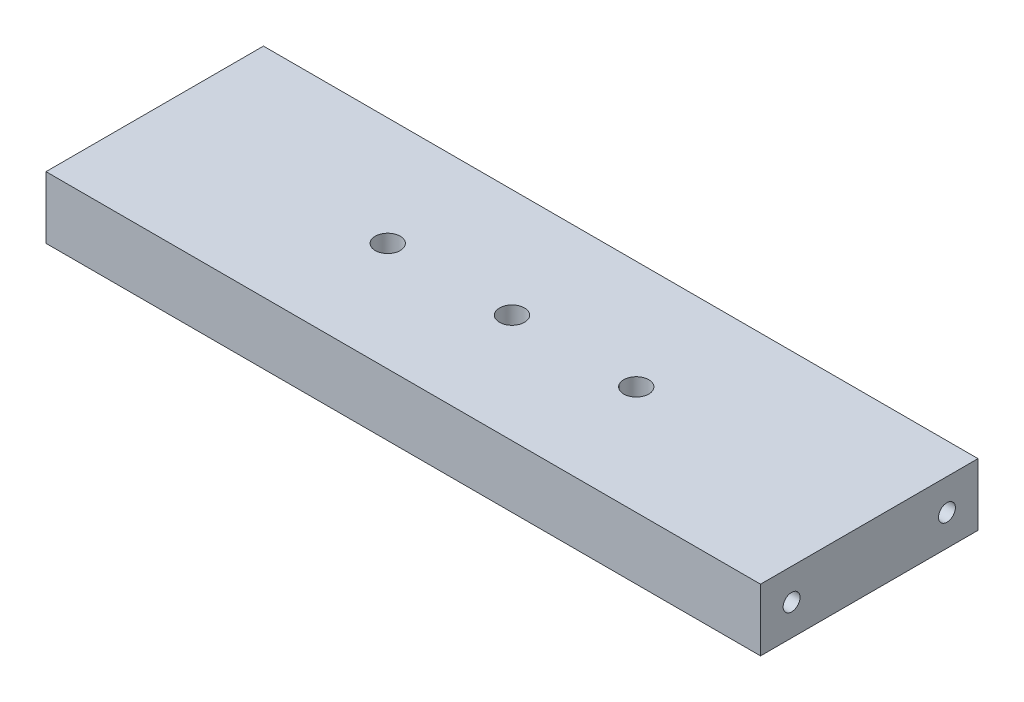
SolidWorks part; units mm, degrees
material "6061 Alloy"
ref_plane "Front Plane" through (0, 0, 0) normal (0, 0, 1) x (1, 0, 0)
ref_plane "Top Plane" through (0, 0, 0) normal (0, 1, 0) x (1, 0, 0)
ref_plane "Right Plane" through (0, 0, 0) normal (1, 0, 0) x (0, 0, -1)
sketch "Sketch2" plane through (0, 0, 0) normal (0, 1, 0) x (1, 0, 0)
  line L1 (-73.025, -22.225) -> (73.025, -22.225)
  line L2 (-73.025, -22.225) -> (-73.025, 22.225)
  line L3 (-73.025, 22.225) -> (73.025, 22.225)
  line L4 (73.025, -22.225) -> (73.025, 22.225)
  line L5 (-73.025, -22.225) -> (73.025, 22.225) construction
  line L6 (-73.025, 22.225) -> (73.025, -22.225) construction
  point P0 (0, 0)
  dimension "D1" = 146.05
  dimension "D2" = 44.45
extrude "Boss-Extrude1" add sketch "Sketch2" along normal blind 12.7
hole_wizard "1/4-20 Tapped Hole1" positions "Sketch4" profile "Sketch5" tap size "1/4-20" standard "ANSI Inch" end condition through all
sketch "Sketch4" plane through (0, 0, 0) normal (0, -1, 0) x (-1, 0, 0)
  point P0 (0, 0)
  point P11 (-25.4, 0)
  point P12 (25.4, 0)
  dimension "D1" = 25.4
  dimension "D2" = 25.4
sketch "Sketch5" plane through (0, 0, 0) normal (1, 0, 0) x (0, 0, -1)
  line L0 (0, 0) -> (0, 12.7)
  line L1 (0, 12.7) -> (2.5527, 12.7)
  line L2 (2.5527, 12.7) -> (2.5527, 0)
  line L5 (2.5527, 0) -> (0, 0)
  line L11 (0, -6.35) -> (0, 107.95) construction
  dimension "Thru Tap Drill Dia." = 5.1054
  dimension "Thru Tap Drill Depth" = 12.7
cosmetic thread "Hole Thread1" parameters "D2"=6.35
cosmetic thread "Hole Thread4" parameters "D2"=6.35
cosmetic thread "Hole Thread5" parameters "D2"=6.35
hole_wizard "#8-32 Tapped Hole1" positions "Sketch6" profile "Sketch7" tap size "#8-32" standard "ANSI Inch"
sketch "Sketch6" plane through (-73.025, 0, 0) normal (-1, 0, 0) x (0, 0, 1)
  line L0 (-22.225, 12.7) -> (-22.225, 0) construction
  line L1 (22.225, 12.7) -> (22.225, 0) construction
  line L2 (-22.225, 0) -> (22.225, 0) construction
  point P0 (-15.875, 6.35)
  point P2 (15.875, 6.35)
  dimension "D1" = 6.35
  dimension "D2" = 6.35
  dimension "D3" = 6.35
  dimension "D4" = 6.35
sketch "Sketch7" plane through (-73.025, 6.35, -15.875) normal (0, 1, 0) x (0, 0, 1)
  line L0 (0, 0) -> (0, 7.3878)
  line L1 (0, 7.3878) -> (1.7272, 6.35)
  line L2 (1.7272, 6.35) -> (1.7272, 0)
  line L5 (1.7272, 0) -> (0, 0)
  line L10 (0, 7.3878) -> (-1.7272, 6.35) construction
  line L11 (0, -6.35) -> (0, 107.95) construction
  dimension "Tap Drill Dia." = 3.4544
  dimension "Tap Drill Depth" = 6.35
  dimension "Drill Angle" = 118
cosmetic thread "Hole Thread2" parameters "D1"=6.35, "D2"=4.1656
cosmetic thread "Hole Thread3" parameters "D1"=6.35, "D2"=4.1656
mirror "Mirror1" about plane through (0, 0, 0) normal (1, 0, 0) of "#8-32 Tapped Hole1"
